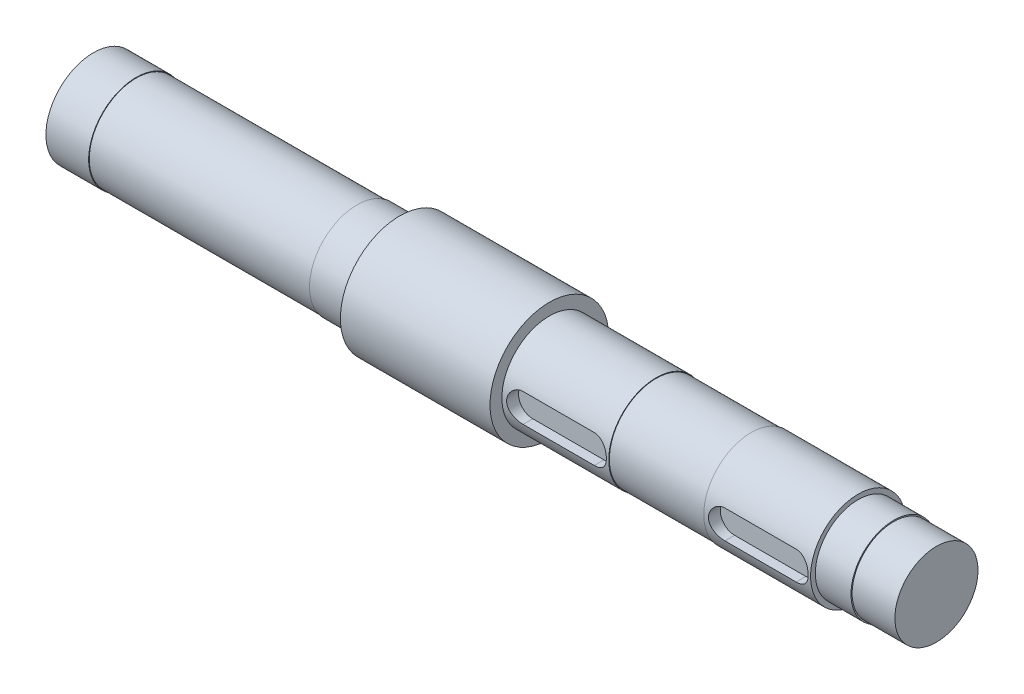
SolidWorks part; units mm, degrees
other "细节项目18"
other "细节项目19"
other "细节项目20"
other "细节项目21"
other "细节项目22"
other "细节项目23"
other "细节项目24"
other "细节项目25"
material "45"
ref_plane "前视基准面" through (0, 0, 0) normal (0, 0, 1) x (1, 0, 0)
ref_plane "上视基准面" through (0, 0, 0) normal (0, 1, 0) x (1, 0, 0)
ref_plane "右视基准面" through (0, 0, 0) normal (1, 0, 0) x (0, 0, -1)
sketch "草图1" plane through (0, 0, 0) normal (0, 0, 1) x (1, 0, 0)
  line L0 (0, 0) -> (-50000, 0) construction
  line L1 (0, 0) -> (0, 50000) construction
  line L2 (0, 0) -> (0, 20)
  line L3 (0, 20) -> (18, 20)
  line L4 (129, 20) -> (129, 25)
  line L5 (129, 25) -> (192, 25)
  line L6 (192, 25) -> (192, 20)
  line L7 (192, 20) -> (237, 20)
  line L8 (337, 18) -> (337, 17.5)
  line L9 (337, 17.5) -> (355, 17.5)
  line L10 (355, 17.5) -> (355, 0)
  line L11 (355, 0) -> (0, 0)
  line L12 (322, 20) -> (322, 18)
  line L13 (322, 18) -> (337, 18)
  line L14 (237, 20) -> (237, 19.75)
  line L15 (237, 19.75) -> (277, 19.75)
  line L16 (277, 19.75) -> (277, 20)
  line L17 (277, 20) -> (322, 20)
  line L18 (111, 20) -> (111, 19.75)
  line L19 (111, 19.75) -> (18, 19.75)
  line L20 (18, 19.75) -> (18, 20)
  line L21 (111, 20) -> (129, 20)
  dimension "D1" = 40
  dimension "D2" = 50
  dimension "D4" = 63
  dimension "D5" = 40
  dimension "D6" = 35
  dimension "D7" = 208
  dimension "D8" = 18
  dimension "D9" = 36
  dimension "D10" = 15
  dimension "D11" = 45
  dimension "D12" = 40
  dimension "D13" = 39.5
  dimension "D14" = 18
  dimension "D15" = 93
  dimension "D16" = 39.5
  dimension "D17" = 355
  dimension "D18" = 18
revolve "旋转1" add sketch "草图1" angle 360 about L0
ref_plane "基准面1" through (0, 0, 15) normal (0, 0, 1) x (1, 0, 0)
sketch "草图2" plane through (0, 0, 15) normal (0, 0, 1) x (1, 0, 0)
  line L0 (0, 0) -> (50000, 0) construction
  line L1 (200, 0) -> (230, 0) construction
  line L2 (200, 6) -> (230, 6)
  line L3 (200, -6) -> (230, -6)
  line L4 (285, 0) -> (315, 0) construction
  line L5 (285, 6) -> (315, 6)
  line L6 (285, -6) -> (315, -6)
  line L7 (192, -20) -> (192, 20) construction
  arc A0 (200, 6) -> (200, -6) centre (200, 0) ccw
  arc A1 (230, -6) -> (230, 6) centre (230, 0) ccw
  arc A2 (285, 6) -> (285, -6) centre (285, 0) ccw
  arc A3 (315, -6) -> (315, 6) centre (315, 0) ccw
  point P5 (215, 0)
  point P10 (300, 0)
  dimension "D1" = 12
  dimension "D2" = 8
  dimension "D3" = 30
  dimension "D4" = 30
  dimension "D5" = 55
extrude "切除-拉伸1" cut sketch "草图2" along normal blind 10
